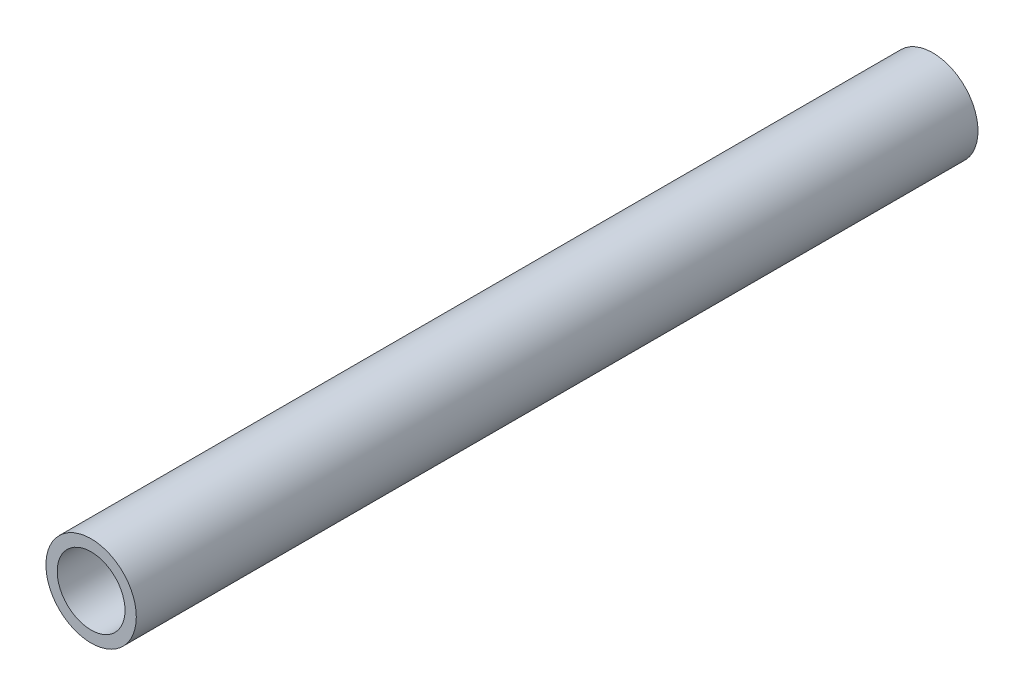
SolidWorks part; units mm, degrees
material "1060 Alloy"
ref_plane "Front Plane" through (0, 0, 0) normal (0, 0, 1) x (1, 0, 0)
ref_plane "Top Plane" through (0, 0, 0) normal (0, 1, 0) x (1, 0, 0)
ref_plane "Right Plane" through (0, 0, 0) normal (1, 0, 0) x (0, 0, -1)
sketch "Sketch2" plane through (0, 0, 0) normal (0, 0, 1) x (1, 0, 0)
  circle A0 centre (0, 0) radius 8
  circle A1 centre (0, 0) radius 6
  dimension "D1" = 16
  dimension "D2" = 2
extrude "Boss-Extrude1" add sketch "Sketch2" along normal mid plane 149
